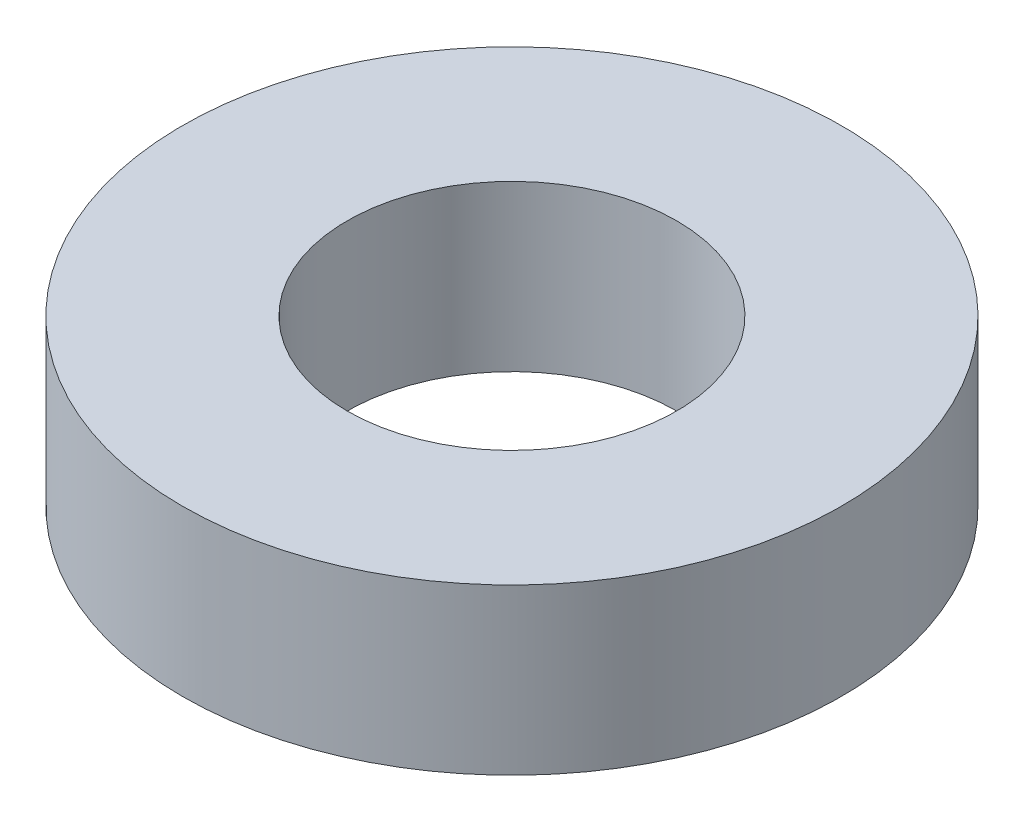
SolidWorks part; units mm, degrees
ref_plane "Front Plane" through (0, 0, 0) normal (0, 0, 1) x (1, 0, 0)
ref_plane "Top Plane" through (0, 0, 0) normal (0, 1, 0) x (1, 0, 0)
ref_plane "Right Plane" through (0, 0, 0) normal (1, 0, 0) x (0, 0, -1)
sketch "Sketch1" plane through (0, 0, 0) normal (0, 1, 0) x (1, 0, 0)
  circle A0 centre (0, 0) radius 12.7
  circle A1 centre (0, 0) radius 6.35
extrude "Boss-Extrude1" add sketch "Sketch1" along normal blind 6.35
sketch "Sketch3" plane through (0, 0, 0) normal (0, -1, 0) x (-1, 0, 0)
  line L0 (0, 0) -> (12.4526, 2.4946) construction
  line L1 (0, 0) -> (12.6226, 1.3998) construction
  line L2 (0, 0) -> (12.6966, 0.2943) construction
  line L3 (0, 0) -> (12.6739, -0.8134) construction
  line L4 (0, 0) -> (12.5548, -1.9149) construction
  line L5 (0, 0) -> (12.3401, -3.0018) construction
  line L6 (0, 0) -> (12.0316, -4.0659) construction
  line L7 (0, 0) -> (11.6314, -5.0991) construction
  line L8 (0, 0) -> (11.1427, -6.0934) construction
  line L9 (0, 0) -> (10.5693, -7.0414) construction
  line L10 (0, 0) -> (9.9153, -7.9357) construction
  line L11 (0, 0) -> (9.186, -8.7697) construction
  line L12 (0, 0) -> (8.3867, -9.537) construction
  line L13 (0, 0) -> (7.5236, -10.2316) construction
  line L14 (0, 0) -> (6.6032, -10.8484) construction
  line L15 (0, 0) -> (5.6326, -11.3826) construction
  line L16 (0, 0) -> (4.6191, -11.8302) construction
  line L17 (0, 0) -> (3.5704, -12.1878) construction
  line L18 (0, 0) -> (2.4946, -12.4526) construction
  line L19 (0, 0) -> (1.3998, -12.6226) construction
  line L20 (0, 0) -> (0.2943, -12.6966) construction
  line L21 (0, 0) -> (-0.8134, -12.6739) construction
  line L22 (0, 0) -> (-1.9149, -12.5548) construction
  line L23 (0, 0) -> (-3.0018, -12.3401) construction
  line L24 (0, 0) -> (-4.0659, -12.0316) construction
  line L25 (0, 0) -> (-5.0991, -11.6314) construction
  line L26 (0, 0) -> (-6.0934, -11.1427) construction
  line L27 (0, 0) -> (-7.0414, -10.5693) construction
  line L28 (0, 0) -> (-7.9357, -9.9153) construction
  line L29 (0, 0) -> (-8.7697, -9.186) construction
  line L30 (0, 0) -> (-9.537, -8.3867) construction
  line L31 (0, 0) -> (-10.2316, -7.5236) construction
  line L32 (0, 0) -> (-10.8484, -6.6032) construction
  line L33 (0, 0) -> (-11.3826, -5.6326) construction
  line L34 (0, 0) -> (-11.8302, -4.6191) construction
  line L35 (0, 0) -> (-12.1878, -3.5704) construction
  line L36 (0, 0) -> (-12.4526, -2.4946) construction
  line L37 (0, 0) -> (-12.6226, -1.3998) construction
  line L38 (0, 0) -> (-12.6966, -0.2943) construction
  line L39 (0, 0) -> (-12.6739, 0.8134) construction
  line L40 (0, 0) -> (-12.5548, 1.9149) construction
  line L41 (0, 0) -> (-12.3401, 3.0018) construction
  line L42 (0, 0) -> (-12.0316, 4.0659) construction
  line L43 (0, 0) -> (-11.6314, 5.0991) construction
  line L44 (0, 0) -> (-11.1427, 6.0934) construction
  line L45 (0, 0) -> (-10.5693, 7.0414) construction
  line L46 (0, 0) -> (-9.9153, 7.9357) construction
  line L47 (0, 0) -> (-9.186, 8.7697) construction
  line L48 (0, 0) -> (-8.3867, 9.537) construction
  line L49 (0, 0) -> (-7.5236, 10.2316) construction
  line L50 (0, 0) -> (-6.6032, 10.8484) construction
  line L51 (0, 0) -> (-5.6326, 11.3826) construction
  line L52 (0, 0) -> (-4.6191, 11.8302) construction
  line L53 (0, 0) -> (-3.5704, 12.1878) construction
  line L54 (0, 0) -> (-2.4946, 12.4526) construction
  line L55 (0, 0) -> (-1.3998, 12.6226) construction
  line L56 (0, 0) -> (-0.2943, 12.6966) construction
  line L57 (0, 0) -> (0.8134, 12.6739) construction
  line L58 (0, 0) -> (1.9149, 12.5548) construction
  line L59 (0, 0) -> (3.0018, 12.3401) construction
  line L60 (0, 0) -> (4.0659, 12.0316) construction
  line L61 (0, 0) -> (5.0991, 11.6314) construction
  line L62 (0, 0) -> (6.0934, 11.1427) construction
  line L63 (0, 0) -> (7.0414, 10.5693) construction
  line L64 (0, 0) -> (7.9357, 9.9153) construction
  line L65 (0, 0) -> (8.7697, 9.186) construction
  line L66 (0, 0) -> (9.537, 8.3867) construction
  line L67 (0, 0) -> (10.2316, 7.5236) construction
  line L68 (0, 0) -> (10.8484, 6.6032) construction
  line L69 (0, 0) -> (11.3826, 5.6326) construction
  line L70 (0, 0) -> (11.8302, 4.6191) construction
  line L71 (0, 0) -> (12.1878, 3.5704) construction
  point P76 (0, 0)
  dimension "D1" = 72
